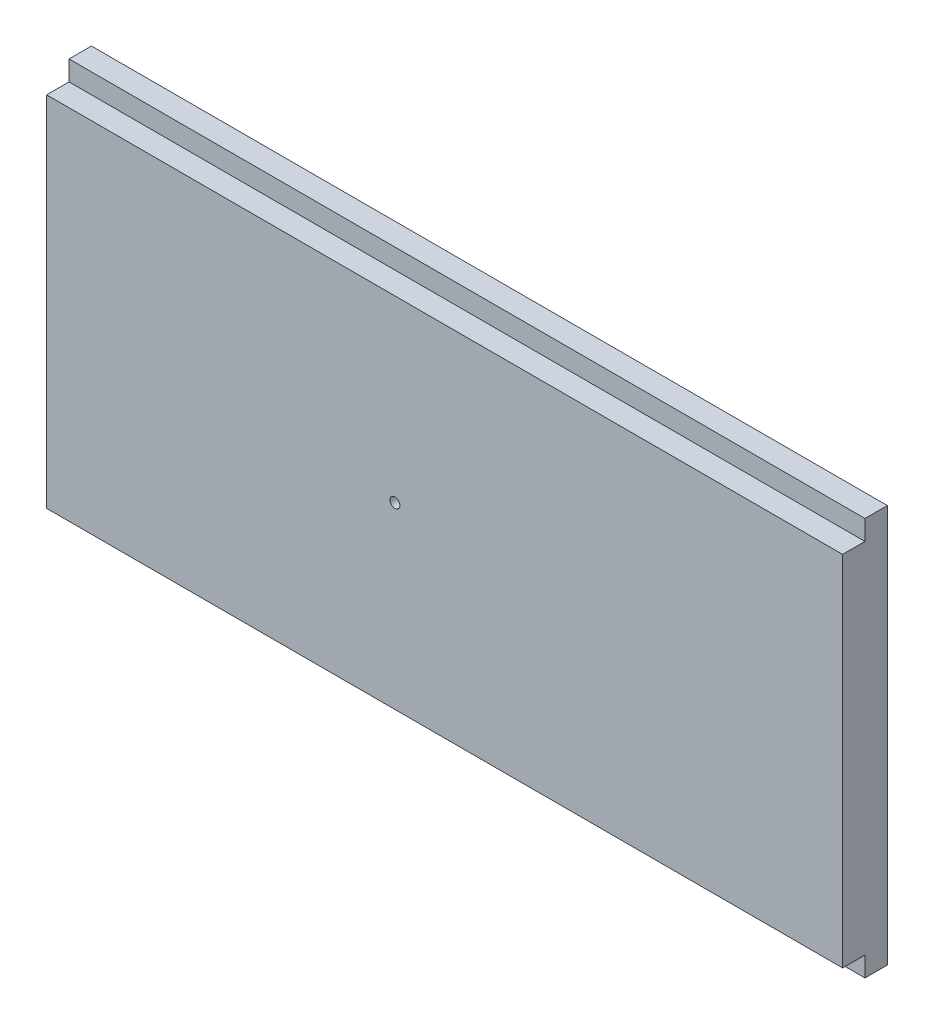
SolidWorks part; units mm, degrees
ref_plane "Front Plane" through (0, 0, 0) normal (1, 0, 0) x (0, 1, 0)
ref_plane "Top Plane" through (0, 0, 0) normal (0, 0, 1) x (0, 1, 0)
ref_plane "Right Plane" through (0, 0, 0) normal (0, 1, 0) x (-1, 0, 0)
sketch "Sketch1" plane through (0, 0, 0) normal (0, 0, 1) x (0, 1, 0)
  line L1 (0, 0) -> (40, 0)
  line L2 (0, 0) -> (0, 80)
  line L3 (0, 80) -> (40, 80)
  line L4 (40, 0) -> (40, 80)
  dimension "D1" = 40
  dimension "D2" = 80
extrude "Boss-Extrude1" add sketch "Sketch1" along normal blind 4.5 contours L3 L4 L1 L2
sketch "Sketch2" plane through (0, 0, 4.5) normal (0, 0, 1) x (1, 0, 0)
  line L0 (-80, 20) -> (0, 20) construction
  line L1 (-80, 0) -> (-80, 40) construction
  line L2 (0, 0) -> (0, 40) construction
  circle A0 centre (-45, 20) radius 0.5
  dimension "D1" = 1
  dimension "D2" = 35
extrude "Cut-Extrude1" cut sketch "Sketch2" against normal through all
sketch "Sketch3" plane through (-80, 0, 0) normal (-1, 0, 0) x (0, -1, 0)
  line L0 (-20, 4.5) -> (-20, 0) construction
  line L1 (0, 4.5) -> (-40, 4.5) construction
  line L2 (0, 0) -> (-40, 0) construction
  line L3 (-40, 4.5) -> (-40, 0) construction
  line L4 (-40, 4.5) -> (-38, 4.5)
  line L5 (-40, 4.5) -> (-40, 2.25)
  line L6 (-40, 2.25) -> (-38, 2.25)
  line L7 (-38, 4.5) -> (-38, 2.25)
  line L8 (0, 2.25) -> (-2, 2.25)
  line L9 (-2, 4.5) -> (-2, 2.25)
  line L10 (0, 4.5) -> (-2, 4.5)
  line L11 (0, 4.5) -> (0, 2.25)
  point P11 (0, 0)
  dimension "D1" = 2
extrude "Cut-Extrude2" cut sketch "Sketch3" against normal through all
